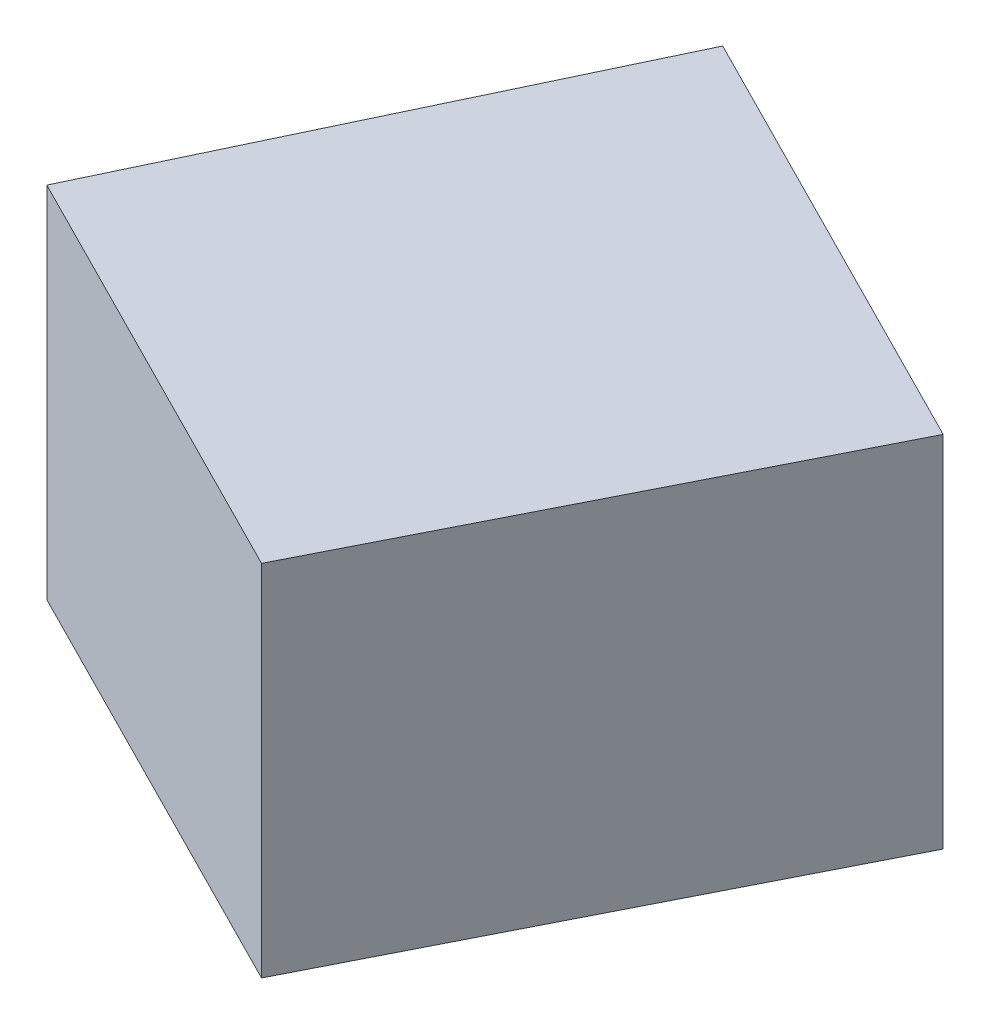
SolidWorks part; units mm, degrees
ref_plane "Front Plane" through (0, 0, 0) normal (0, 0, 1) x (1, 0, 0)
ref_plane "Top Plane" through (0, 0, 0) normal (0, 1, 0) x (1, 0, 0)
ref_plane "Right Plane" through (0, 0, 0) normal (1, 0, 0) x (0, 0, -1)
sketch "Sketch1" plane through (0, 0, 0) normal (0, 1, 0) x (1, 0, 0)
  line L0 (-61.0566, -7.2804) -> (7.9871, -42.2393)
  line L1 (7.9871, -42.2393) -> (44.357, 29.5913)
  line L2 (44.357, 29.5913) -> (-26.5348, 65.4859)
  line L3 (-26.5348, 65.4859) -> (-61.0566, -7.2804)
extrude "Boss-Extrude1" add sketch "Sketch1" along normal blind 57
move or copy body "Body-Move/Copy1" bodies to move or copy 101 copy no translate (225.9074, -44.5021, 261.851) parameters "D1"=225.9074, "D2"=44.5021, "D3"=261.851
